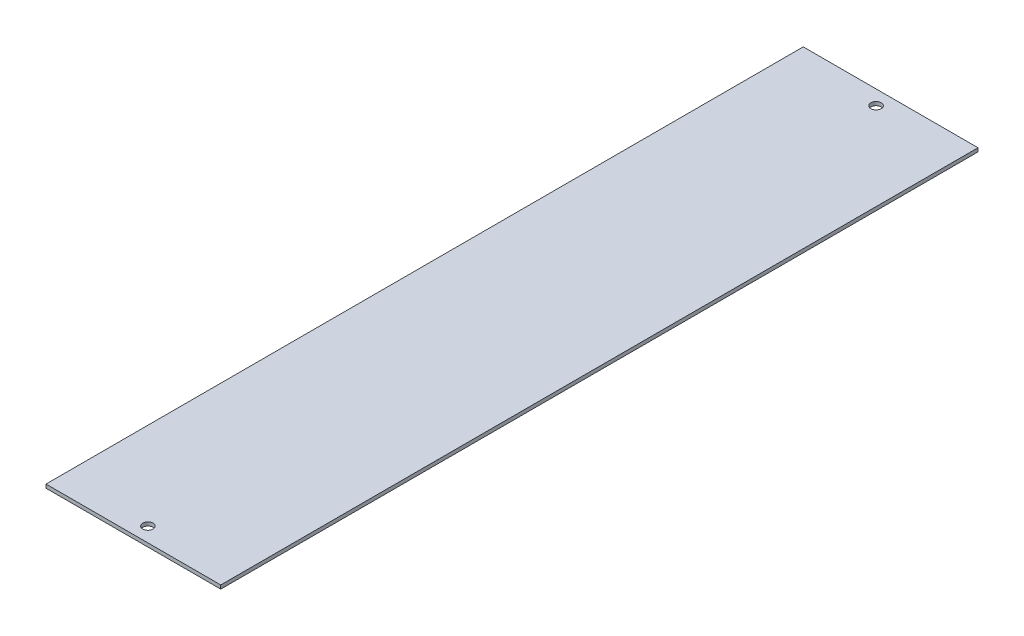
SolidWorks part; units mm, degrees
material "ABS PC"
ref_plane "Front Plane" through (0, 0, 0) normal (0, 0, 1) x (1, 0, 0)
ref_plane "Top Plane" through (0, 0, 0) normal (0, 1, 0) x (1, 0, 0)
ref_plane "Right Plane" through (0, 0, 0) normal (1, 0, 0) x (0, 0, -1)
sketch "Sketch1" plane through (0, 0, 0) normal (0, 1, 0) x (1, 0, 0)
  line L0 (-38.1, 0) -> (-38.1, -21.7369) construction
  line L1 (0, 0) -> (-76.2, 0)
  line L2 (0, 0) -> (0, -330.2)
  line L3 (0, -330.2) -> (-76.2, -330.2)
  line L4 (-76.2, 0) -> (-76.2, -330.2)
  circle A0 centre (-38.1, -6.35) radius 2.25
  circle A1 centre (-38.1, -323.85) radius 2.25
  point P6 (-38.1, 0)
  dimension "D3" = 4.5
  dimension "D6" = 4.5
  dimension "D1" = 76.2
  dimension "D2" = 330.2
  dimension "D4" = 6.35
  dimension "D5" = 6.35
extrude "Boss-Extrude1" add sketch "Sketch1" along normal blind 1.5875
